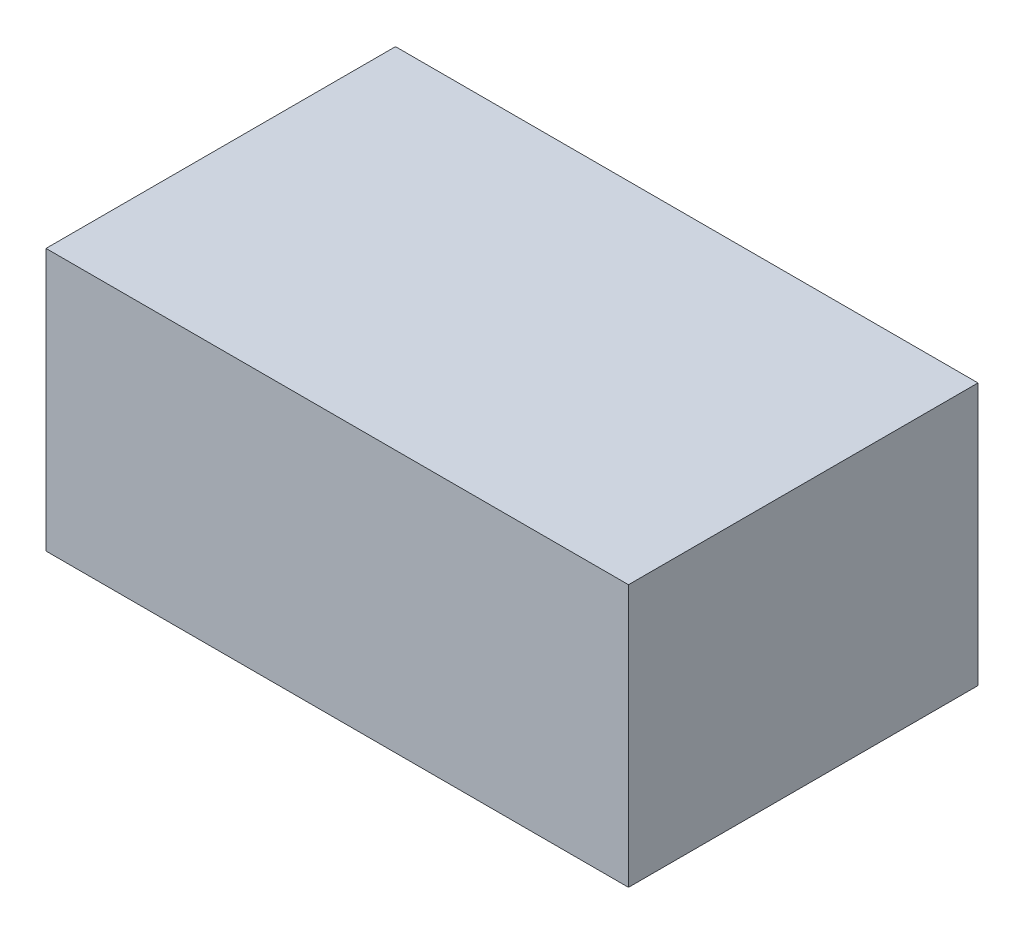
SolidWorks part; units mm, degrees
ref_plane "Front Plane" through (0, 0, 0) normal (0, 0, 1) x (1, 0, 0)
ref_plane "Top Plane" through (0, 0, 0) normal (0, 1, 0) x (1, 0, 0)
ref_plane "Right Plane" through (0, 0, 0) normal (1, 0, 0) x (0, 0, -1)
sketch "Sketch1" plane through (0, 0, 0) normal (0, 1, 0) x (1, 0, 0)
  line L1 (-178.5863, 127.6133) -> (221.4137, 127.6133)
  line L2 (-178.5863, 127.6133) -> (-178.5863, -112.3867)
  line L3 (-178.5863, -112.3867) -> (221.4137, -112.3867)
  line L4 (221.4137, 127.6133) -> (221.4137, -112.3867)
  dimension "D1" = 400
  dimension "D2" = 240
extrude "Boss-Extrude1" add sketch "Sketch1" along normal blind 180
